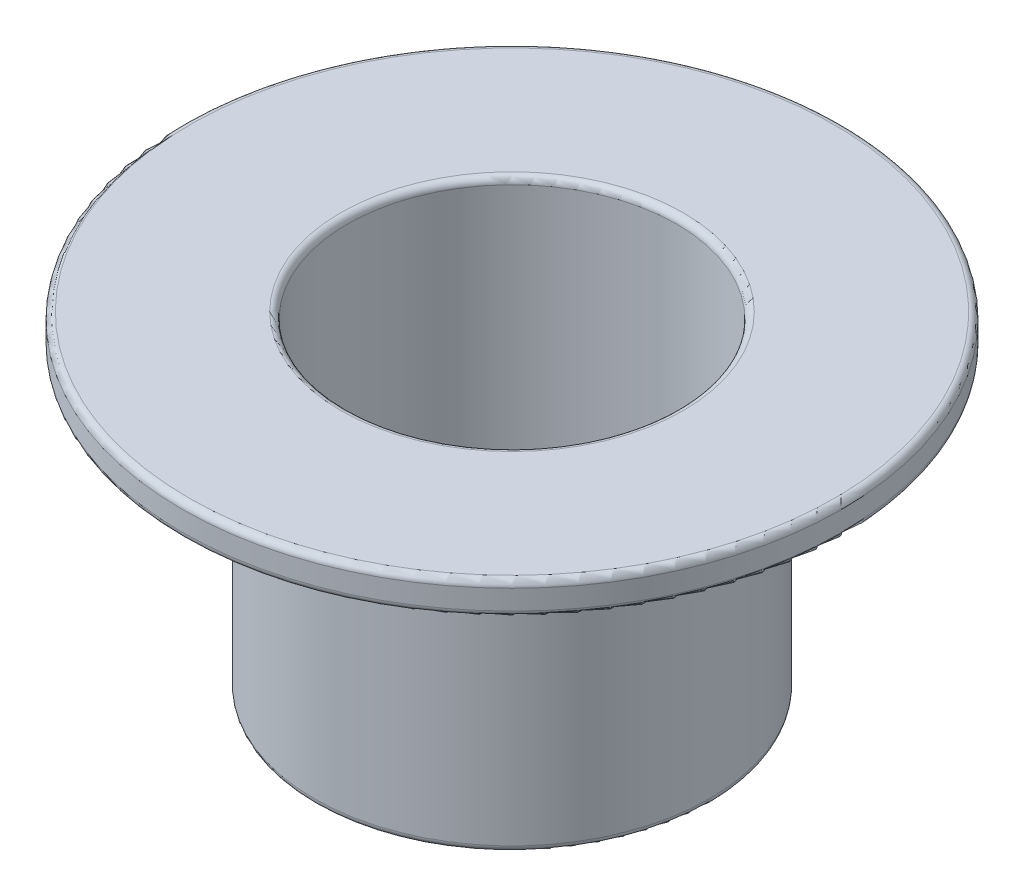
SolidWorks part; units mm, degrees
material "Delrin 2700 NC010, Low Viscosity Acetal Copolymer (SS)"
ref_plane "Front Plane" through (0, 0, 0) normal (0, 0, 1) x (1, 0, 0)
ref_plane "Top Plane" through (0, 0, 0) normal (0, 1, 0) x (1, 0, 0)
ref_plane "Right Plane" through (0, 0, 0) normal (1, 0, 0) x (0, 0, -1)
sketch "Sketch1" plane through (0, 0, 0) normal (0, 1, 0) x (1, 0, 0)
  circle A0 centre (0, 0) radius 2.5
  circle A1 centre (0, 0) radius 3
  dimension "D1" = 5
  dimension "D2" = 6
extrude "Boss-Extrude1" add sketch "Sketch1" along normal blind 4.5
sketch "Sketch2" plane through (0, 4.5, 0) normal (0, 1, 0) x (1, 0, 0)
  circle A0 centre (0, 0) radius 2.5
  circle A1 centre (0, 0) radius 5
  dimension "D1" = 10
extrude "Boss-Extrude2" add sketch "Sketch2" along normal blind 0.5
fillet "Fillet1" radius 0.1 5 edges at (0, 5, 5) (0, 4.5, 5) (0, 0, 2.5) (0, 0, 3) (0, 5, 2.5)
